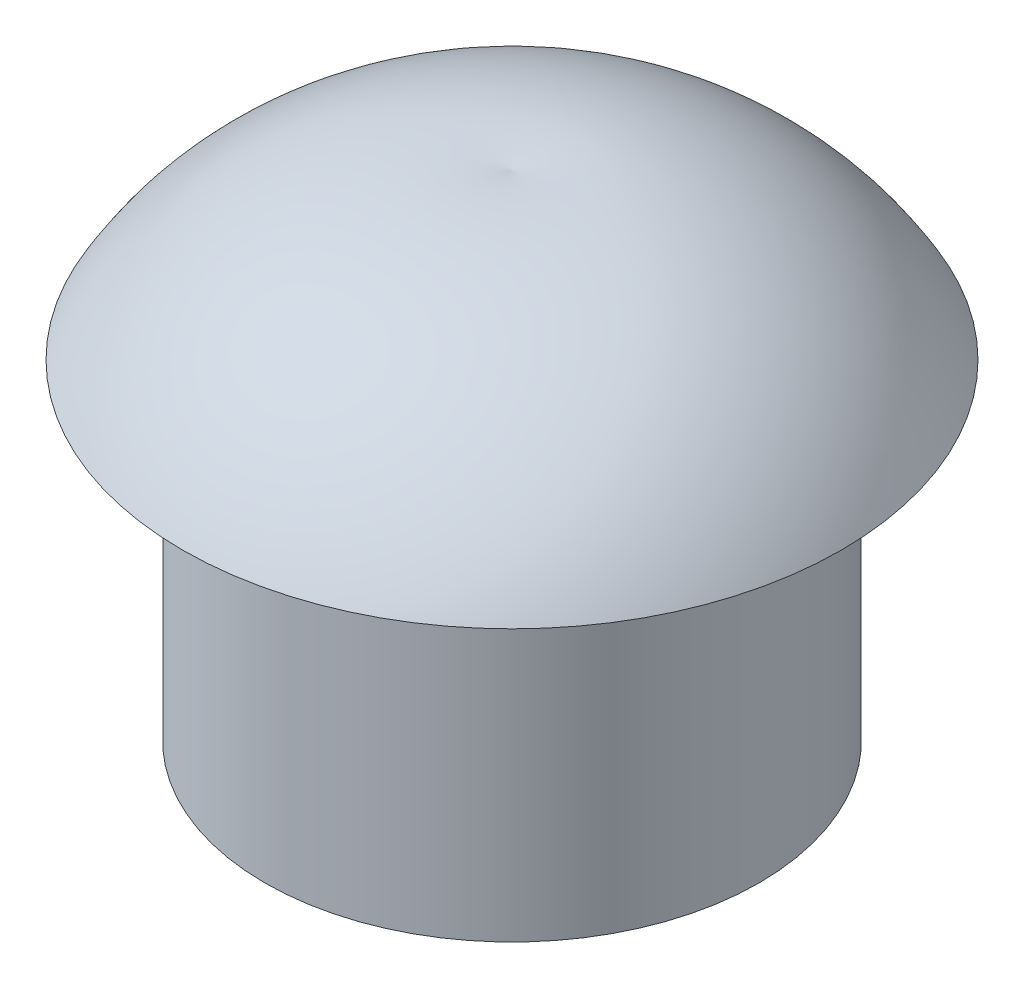
SolidWorks part; units mm, degrees
material "Plain Carbon Steel"
ref_plane "Front Plane" through (0, 0, 0) normal (0, 0, 1) x (1, 0, 0)
ref_plane "Top Plane" through (0, 0, 0) normal (0, 1, 0) x (1, 0, 0)
ref_plane "Right Plane" through (0, 0, 0) normal (1, 0, 0) x (0, 0, -1)
sketch "Sketch1" plane through (0, 0, 0) normal (0, 1, 0) x (1, 0, 0)
  circle A0 centre (0, 0) radius 1.5
  dimension "D1" = 3
extrude "Boss-Extrude1" add sketch "Sketch1" against normal blind 2
sketch "Sketch3" plane through (0, 0, 0) normal (0, 0, 1) x (1, 0, 0)
  line L0 (0, 0) -> (2, 0)
  line L1 (0, 0) -> (0, 1)
  arc A0 (2, 0) -> (0, 1) centre (0.2584, -0.9832) ccw
  point P6 (0, 0)
  point P7 (0, 0)
  dimension "D3" = 2
  dimension "D1" = 1
  dimension "D2" = 2
revolve "Revolve1" add sketch "Sketch3" angle 360 about L1
